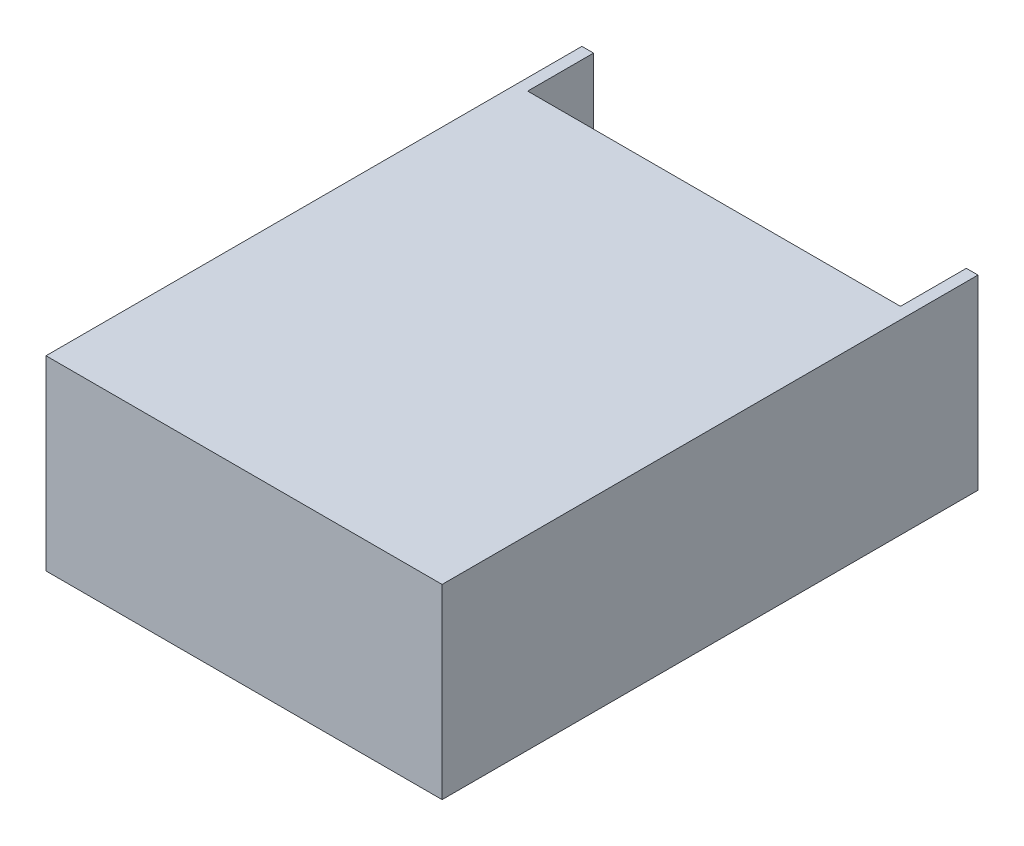
SolidWorks part; units mm, degrees
ref_plane "前视基准面" through (0, 0, 0) normal (0, 0, 1) x (1, 0, 0)
ref_plane "上视基准面" through (0, 0, 0) normal (0, 1, 0) x (1, 0, 0)
ref_plane "右视基准面" through (0, 0, 0) normal (1, 0, 0) x (0, 0, -1)
sketch "草图1" plane through (0, 0, 0) normal (0, 1, 0) x (1, 0, 0)
  line L1 (0, 0) -> (17, 0)
  line L2 (0, 0) -> (0, 23)
  line L3 (0, 23) -> (17, 23)
  line L4 (17, 0) -> (17, 23)
  dimension "D1" = 23
  dimension "D2" = 17
extrude "凸台-拉伸1" add sketch "草图1" along normal blind 0.5 contours L2 L1 L4 L3
sketch "草图2" plane through (0, 0.5, 0) normal (0, 1, 0) x (1, 0, 0)
  line L0 (0, 23) -> (17, 23) construction
  line L1 (0, 0) -> (0.5, 0)
  line L2 (0, 0) -> (0, 23)
  line L3 (0, 23) -> (0.5, 23)
  line L4 (0.5, 0) -> (0.5, 23)
  line L6 (16.5, 23) -> (17, 23)
  line L7 (16.5, 23) -> (16.5, 0)
  line L8 (16.5, 0) -> (17, 0)
  line L9 (17, 23) -> (17, 0)
  dimension "D1" = 0.5
  dimension "D2" = 0.5
extrude "凸台-拉伸2" add sketch "草图2" along normal blind 7.5
sketch "草图3" plane through (0, 0.5, 0) normal (0, 1, 0) x (1, 0, 0)
  line L0 (16.5, 23) -> (16.5, 0) construction
  line L1 (0.5, 0) -> (16.5, 0)
  line L2 (0.5, 0) -> (0.5, 20.1723)
  line L3 (0.5, 20.1723) -> (16.5, 20.1723)
  line L4 (16.5, 0) -> (16.5, 20.1723)
extrude "凸台-拉伸3" add sketch "草图3" along normal blind 7.5
sketch "草图4" plane through (0, 0.5, 0) normal (0, 1, 0) x (1, 0, 0)
  line L0 (0.5, 23) -> (16.5, 23) construction
  line L1 (3.0445, 23) -> (5.5385, 23)
  line L2 (3.0445, 23) -> (3.0445, 23.4576)
  line L3 (3.0445, 23.4576) -> (5.5385, 23.4576)
  line L4 (5.5385, 23) -> (5.5385, 23.4576)
  line L6 (10.7861, 23) -> (13.1501, 23)
  line L7 (10.7861, 23) -> (10.7861, 23.4576)
  line L8 (10.7861, 23.4576) -> (13.1501, 23.4576)
  line L9 (13.1501, 23) -> (13.1501, 23.4576)
extrude "凸台-拉伸4" add sketch "草图4" against normal blind 0.5
